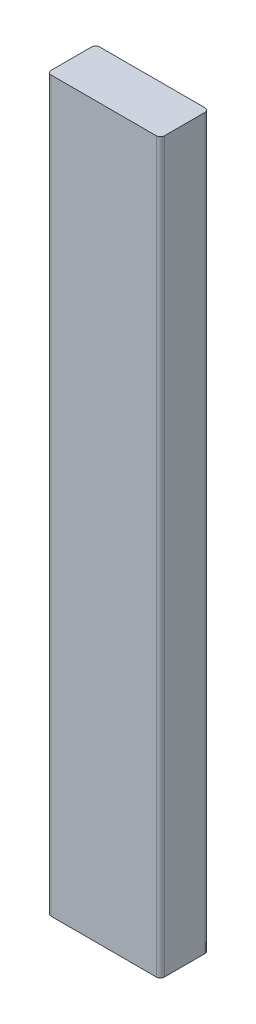
SolidWorks part; units mm, degrees
material "Pine"
ref_plane "Front Plane" through (0, 0, 0) normal (0, 0, 1) x (1, 0, 0)
ref_plane "Top Plane" through (0, 0, 0) normal (0, 1, 0) x (1, 0, 0)
ref_plane "Right Plane" through (0, 0, 0) normal (1, 0, 0) x (0, 0, -1)
sketch "Sketch1" plane through (0, 0, 0) normal (0, 1, 0) x (1, 0, 0)
  line L1 (-44.45, 19.05) -> (44.45, 19.05)
  line L2 (-44.45, 19.05) -> (-44.45, -19.05)
  line L3 (-44.45, -19.05) -> (44.45, -19.05)
  line L4 (44.45, 19.05) -> (44.45, -19.05)
  line L5 (-44.45, 19.05) -> (44.45, -19.05) construction
  line L6 (-44.45, -19.05) -> (44.45, 19.05) construction
  point P0 (0, 0)
  dimension "D1" = 88.9
  dimension "D2" = 38.1
extrude "Boss-Extrude1" add sketch "Sketch1" along normal blind 571.5
fillet "Fillet1" radius 3.175 4 edges at (-44.45, 285.75, 19.05) (-44.45, 285.75, -19.05) (44.45, 285.75, -19.05) (44.45, 285.75, 19.05)
